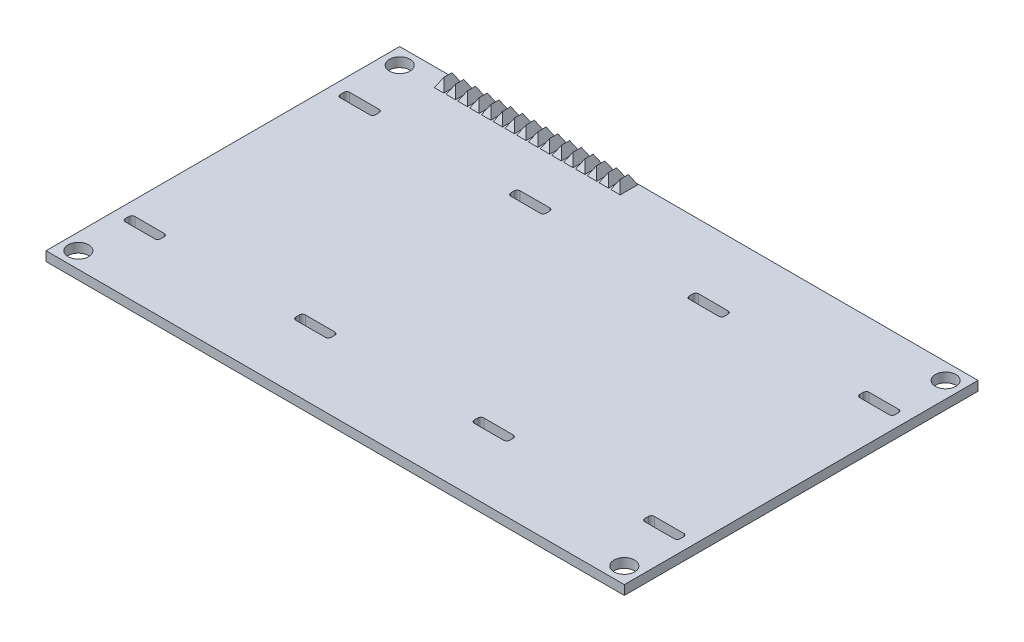
SolidWorks part; units mm, degrees
ref_plane "Front Plane" through (0, 0, 0) normal (0, 0, 1) x (1, 0, 0)
ref_plane "Top Plane" through (0, 0, 0) normal (0, 1, 0) x (1, 0, 0)
ref_plane "Right Plane" through (0, 0, 0) normal (1, 0, 0) x (0, 0, -1)
sketch "Sketch1" plane through (0, 0, 0) normal (0, 1, 0) x (1, 0, 0)
  line L0 (1, 57.4) -> (1, 50.0873) construction
  line L1 (0, 0) -> (98.35, 0)
  line L2 (0, 0) -> (0, 60.15)
  line L3 (0, 60.15) -> (98.35, 60.15)
  line L4 (98.35, 0) -> (98.35, 60.15)
  line L5 (2.75, 59.15) -> (12.6267, 59.15) construction
  line L6 (11, 60.05) -> (12.6, 60.05)
  line L7 (9, 60.05) -> (10.6, 60.05)
  line L8 (9, 60.05) -> (9, 57.05)
  line L9 (9, 57.05) -> (10.6, 57.05)
  line L10 (10.6, 60.05) -> (10.6, 57.05)
  line L11 (12.6, 60.05) -> (12.6, 57.05)
  line L12 (11, 57.05) -> (12.6, 57.05)
  line L13 (11, 60.05) -> (11, 57.05)
  line L14 (13, 60.05) -> (14.6, 60.05)
  line L15 (14.6, 60.05) -> (14.6, 57.05)
  line L16 (13, 57.05) -> (14.6, 57.05)
  line L17 (13, 60.05) -> (13, 57.05)
  line L18 (15, 60.05) -> (16.6, 60.05)
  line L19 (16.6, 60.05) -> (16.6, 57.05)
  line L20 (15, 57.05) -> (16.6, 57.05)
  line L21 (15, 60.05) -> (15, 57.05)
  line L22 (17, 60.05) -> (18.6, 60.05)
  line L23 (18.6, 60.05) -> (18.6, 57.05)
  line L24 (17, 57.05) -> (18.6, 57.05)
  line L25 (17, 60.05) -> (17, 57.05)
  line L26 (19, 60.05) -> (20.6, 60.05)
  line L27 (20.6, 60.05) -> (20.6, 57.05)
  line L28 (19, 57.05) -> (20.6, 57.05)
  line L29 (19, 60.05) -> (19, 57.05)
  line L30 (21, 60.05) -> (22.6, 60.05)
  line L31 (22.6, 60.05) -> (22.6, 57.05)
  line L32 (21, 57.05) -> (22.6, 57.05)
  line L33 (21, 60.05) -> (21, 57.05)
  line L34 (23, 60.05) -> (24.6, 60.05)
  line L35 (24.6, 60.05) -> (24.6, 57.05)
  line L36 (23, 57.05) -> (24.6, 57.05)
  line L37 (23, 60.05) -> (23, 57.05)
  line L38 (25, 60.05) -> (26.6, 60.05)
  line L39 (26.6, 60.05) -> (26.6, 57.05)
  line L40 (25, 57.05) -> (26.6, 57.05)
  line L41 (25, 60.05) -> (25, 57.05)
  line L42 (27, 60.05) -> (28.6, 60.05)
  line L43 (28.6, 60.05) -> (28.6, 57.05)
  line L44 (27, 57.05) -> (28.6, 57.05)
  line L45 (27, 60.05) -> (27, 57.05)
  line L46 (29, 60.05) -> (30.6, 60.05)
  line L47 (30.6, 60.05) -> (30.6, 57.05)
  line L48 (29, 57.05) -> (30.6, 57.05)
  line L49 (29, 60.05) -> (29, 57.05)
  line L50 (31, 60.05) -> (32.6, 60.05)
  line L51 (32.6, 60.05) -> (32.6, 57.05)
  line L52 (31, 57.05) -> (32.6, 57.05)
  line L53 (31, 60.05) -> (31, 57.05)
  line L54 (33, 60.05) -> (34.6, 60.05)
  line L55 (34.6, 60.05) -> (34.6, 57.05)
  line L56 (33, 57.05) -> (34.6, 57.05)
  line L57 (33, 60.05) -> (33, 57.05)
  line L58 (35, 60.05) -> (36.6, 60.05)
  line L59 (36.6, 60.05) -> (36.6, 57.05)
  line L60 (35, 57.05) -> (36.6, 57.05)
  line L61 (35, 60.05) -> (35, 57.05)
  line L62 (37, 60.05) -> (38.6, 60.05)
  line L63 (38.6, 60.05) -> (38.6, 57.05)
  line L64 (37, 57.05) -> (38.6, 57.05)
  line L65 (37, 60.05) -> (37, 57.05)
  line L66 (39, 60.05) -> (40.6, 60.05)
  line L67 (40.6, 60.05) -> (40.6, 57.05)
  line L68 (39, 57.05) -> (40.6, 57.05)
  line L69 (39, 60.05) -> (39, 57.05)
  line L70 (49.175, 60.15) -> (49.175, 0) construction
  line L71 (0, 30.075) -> (98.35, 30.075) construction
  line L72 (95.6, 59.15) -> (85.7233, 59.15) construction
  line L73 (97.35, 57.4) -> (97.35, 50.0873) construction
  line L74 (2.75, 1) -> (12.6267, 1) construction
  line L75 (1, 2.75) -> (1, 10.0627) construction
  line L76 (61.85, 49.15) -> (66.85, 49.15)
  line L77 (90.85, 49.15) -> (95.85, 49.15)
  line L78 (90.35, 48.65) -> (90.35, 48.05)
  line L79 (90.85, 47.55) -> (95.85, 47.55)
  line L80 (96.35, 48.65) -> (96.35, 48.05)
  line L81 (61.35, 48.65) -> (61.35, 48.05)
  line L82 (61.85, 47.55) -> (66.85, 47.55)
  line L83 (67.35, 48.65) -> (67.35, 48.05)
  line L84 (31, 48.65) -> (31, 48.05)
  line L85 (36.5, 47.55) -> (31.5, 47.55)
  line L86 (37, 48.65) -> (37, 48.05)
  line L87 (2, 48.65) -> (2, 48.05)
  line L88 (7.5, 47.55) -> (2.5, 47.55)
  line L89 (8, 48.65) -> (8, 48.05)
  line L90 (7.5, 49.15) -> (2.5, 49.15)
  line L91 (36.5, 49.15) -> (31.5, 49.15)
  line L92 (67.35, 11.5) -> (67.35, 12.1)
  line L93 (61.85, 12.6) -> (66.85, 12.6)
  line L94 (61.35, 11.5) -> (61.35, 12.1)
  line L95 (96.35, 11.5) -> (96.35, 12.1)
  line L96 (90.85, 12.6) -> (95.85, 12.6)
  line L97 (90.35, 11.5) -> (90.35, 12.1)
  line L98 (90.85, 11) -> (95.85, 11)
  line L99 (61.85, 11) -> (66.85, 11)
  line L100 (36.5, 11) -> (31.5, 11)
  line L101 (7.5, 11) -> (2.5, 11)
  line L102 (8, 11.5) -> (8, 12.1)
  line L103 (7.5, 12.6) -> (2.5, 12.6)
  line L104 (2, 11.5) -> (2, 12.1)
  line L105 (37, 11.5) -> (37, 12.1)
  line L106 (36.5, 12.6) -> (31.5, 12.6)
  line L107 (31, 11.5) -> (31, 12.1)
  circle A0 centre (2.75, 57.4) radius 1.75
  circle A1 centre (95.6, 57.4) radius 1.75
  circle A2 centre (95.6, 2.75) radius 1.75
  circle A3 centre (2.75, 2.75) radius 1.75
  arc A4 (95.85, 49.15) -> (96.35, 48.65) centre (95.85, 48.65) cw
  arc A5 (95.85, 47.55) -> (96.35, 48.05) centre (95.85, 48.05) ccw
  arc A6 (90.35, 48.05) -> (90.85, 47.55) centre (90.85, 48.05) ccw
  arc A7 (90.85, 49.15) -> (90.35, 48.65) centre (90.85, 48.65) ccw
  arc A8 (66.85, 49.15) -> (67.35, 48.65) centre (66.85, 48.65) cw
  arc A9 (66.85, 47.55) -> (67.35, 48.05) centre (66.85, 48.05) ccw
  arc A10 (61.35, 48.05) -> (61.85, 47.55) centre (61.85, 48.05) ccw
  arc A11 (61.85, 49.15) -> (61.35, 48.65) centre (61.85, 48.65) ccw
  arc A12 (36.5, 49.15) -> (37, 48.65) centre (36.5, 48.65) cw
  arc A13 (37, 48.05) -> (36.5, 47.55) centre (36.5, 48.05) cw
  arc A14 (31.5, 47.55) -> (31, 48.05) centre (31.5, 48.05) cw
  arc A15 (31.5, 49.15) -> (31, 48.65) centre (31.5, 48.65) ccw
  arc A16 (7.5, 49.15) -> (8, 48.65) centre (7.5, 48.65) cw
  arc A17 (8, 48.05) -> (7.5, 47.55) centre (7.5, 48.05) cw
  arc A18 (2.5, 47.55) -> (2, 48.05) centre (2.5, 48.05) cw
  arc A19 (2.5, 49.15) -> (2, 48.65) centre (2.5, 48.65) ccw
  arc A20 (61.85, 11) -> (61.35, 11.5) centre (61.85, 11.5) cw
  arc A21 (61.35, 12.1) -> (61.85, 12.6) centre (61.85, 12.1) cw
  arc A22 (66.85, 12.6) -> (67.35, 12.1) centre (66.85, 12.1) cw
  arc A23 (66.85, 11) -> (67.35, 11.5) centre (66.85, 11.5) ccw
  arc A24 (90.85, 11) -> (90.35, 11.5) centre (90.85, 11.5) cw
  arc A25 (90.35, 12.1) -> (90.85, 12.6) centre (90.85, 12.1) cw
  arc A26 (95.85, 12.6) -> (96.35, 12.1) centre (95.85, 12.1) cw
  arc A27 (95.85, 11) -> (96.35, 11.5) centre (95.85, 11.5) ccw
  arc A28 (2.5, 11) -> (2, 11.5) centre (2.5, 11.5) cw
  arc A29 (2.5, 12.6) -> (2, 12.1) centre (2.5, 12.1) ccw
  arc A30 (8, 12.1) -> (7.5, 12.6) centre (7.5, 12.1) ccw
  arc A31 (7.5, 11) -> (8, 11.5) centre (7.5, 11.5) ccw
  arc A32 (31.5, 11) -> (31, 11.5) centre (31.5, 11.5) cw
  arc A33 (31.5, 12.6) -> (31, 12.1) centre (31.5, 12.1) ccw
  arc A34 (37, 12.1) -> (36.5, 12.6) centre (36.5, 12.1) ccw
  arc A35 (36.5, 11) -> (37, 11.5) centre (36.5, 11.5) ccw
  point P99 (96.35, 49.15)
  point P102 (96.35, 47.55)
  point P107 (90.35, 49.15)
  point P108 (64.35, 49.15)
  point P109 (93.35, 49.15)
  point P146 (8, 49.15)
  point P147 (2, 47.55)
  point P148 (2, 49.15)
  point P173 (90.35, 11)
  point P174 (96.35, 12.6)
  point P175 (96.35, 11)
  point P200 (2, 11)
  point P201 (2, 12.6)
  point P202 (8, 11)
  dimension "D3" = 3.5
  dimension "D17" = 0.5
  dimension "D1" = 98.35
  dimension "D2" = 60.15
  dimension "D4" = 1
  dimension "D5" = 1
  dimension "D6" = 9
  dimension "D7" = 1.6
  dimension "D8" = 3
  dimension "D10" = 0.1
  dimension "D11" = 0.1
  dimension "D12" = 0.4
  dimension "D13" = 11
  dimension "D14" = 6
  dimension "D15" = 1.6
  dimension "D16" = 2
  dimension "D19" = 29
  dimension "D20" = 11
  dimension "D9" = 16
  dimension "D18" = 2
extrude "Boss-Extrude1" add sketch "Sketch1" along normal blind 1.6 contours L10 L7 L8 L9 | L6 L13 L12 L11 | L14 L17 L16 L15 | L18 L21 L20 L19 | L22 L25 L24 L23 | L30 L33 L32 L31 | L26 L29 L28 L27 | L34 L37 L36 L35 | L38 L41 L40 L39 | L42 L45 L44 L43 | L46 L49 L48 L47 | L50 L53 L52 L51 | L54 L57 L56 L55 | L58 L61 L60 L59 | L62 L65 L64 L63 | L66 L69 L68 L67 | L1 L4 L3 L2 A35 L100 A32 L107 A33 L106 A34 L105 A31 L101 A28 L104 A29 L103 A30 L102 A27 L98 A24 L97 A25 L96 A26 L95 A23 L99 A20 L94 A21 L93 A22 L92 A19 L90 A16 L89 A17 L88 A18 L87 A15
sketch "Sketch2" plane through (0, 1.6, 0) normal (0, 1, 0) x (1, 0, 0)
  line L4 (0, 0) -> (98.35, 0)
  line L5 (98.35, 0) -> (98.35, 60.15)
  line L6 (98.35, 60.15) -> (0, 60.15)
  line L7 (0, 60.15) -> (0, 0)
  line L8 (0, 0) -> (98.35, 0)
  line L9 (98.35, 0) -> (98.35, 60.15)
  line L10 (98.35, 60.15) -> (0, 60.15)
  line L11 (0, 60.15) -> (0, 0)
  line L12 (10.6, 60.05) -> (9, 60.05)
  line L13 (10.6, 57.05) -> (10.6, 60.05)
  line L14 (9, 57.05) -> (10.6, 57.05)
  line L15 (9, 60.05) -> (9, 57.05)
  line L16 (10.6, 60.05) -> (9, 60.05)
  line L17 (10.6, 57.05) -> (10.6, 60.05)
  line L18 (9, 57.05) -> (10.6, 57.05)
  line L19 (9, 60.05) -> (9, 57.05)
  line L20 (0, 0) -> (98.35, 0)
  line L21 (98.35, 0) -> (98.35, 60.15)
  line L22 (98.35, 60.15) -> (0, 60.15)
  line L23 (0, 60.15) -> (0, 0)
  line L24 (0, 0) -> (98.35, 0)
  line L25 (98.35, 0) -> (98.35, 60.15)
  line L26 (98.35, 60.15) -> (0, 60.15)
  line L27 (0, 60.15) -> (0, 0)
  line L28 (16.6, 60.05) -> (15, 60.05)
  line L29 (16.6, 57.05) -> (16.6, 60.05)
  line L30 (15, 57.05) -> (16.6, 57.05)
  line L31 (15, 60.05) -> (15, 57.05)
  line L32 (16.6, 60.05) -> (15, 60.05)
  line L33 (16.6, 57.05) -> (16.6, 60.05)
  line L34 (15, 57.05) -> (16.6, 57.05)
  line L35 (15, 60.05) -> (15, 57.05)
  line L36 (14.6, 60.05) -> (13, 60.05)
  line L37 (14.6, 57.05) -> (14.6, 60.05)
  line L38 (13, 57.05) -> (14.6, 57.05)
  line L39 (13, 60.05) -> (13, 57.05)
  line L40 (14.6, 60.05) -> (13, 60.05)
  line L41 (14.6, 57.05) -> (14.6, 60.05)
  line L42 (13, 57.05) -> (14.6, 57.05)
  line L43 (13, 60.05) -> (13, 57.05)
  line L44 (12.6, 60.05) -> (11, 60.05)
  line L45 (12.6, 57.05) -> (12.6, 60.05)
  line L46 (11, 57.05) -> (12.6, 57.05)
  line L47 (11, 60.05) -> (11, 57.05)
  line L48 (12.6, 60.05) -> (11, 60.05)
  line L49 (12.6, 57.05) -> (12.6, 60.05)
  line L50 (11, 57.05) -> (12.6, 57.05)
  line L51 (11, 60.05) -> (11, 57.05)
  line L52 (24.6, 60.05) -> (23, 60.05)
  line L53 (24.6, 57.05) -> (24.6, 60.05)
  line L54 (23, 57.05) -> (24.6, 57.05)
  line L55 (23, 60.05) -> (23, 57.05)
  line L56 (24.6, 60.05) -> (23, 60.05)
  line L57 (24.6, 57.05) -> (24.6, 60.05)
  line L58 (23, 57.05) -> (24.6, 57.05)
  line L59 (23, 60.05) -> (23, 57.05)
  line L60 (22.6, 60.05) -> (21, 60.05)
  line L61 (22.6, 57.05) -> (22.6, 60.05)
  line L62 (21, 57.05) -> (22.6, 57.05)
  line L63 (21, 60.05) -> (21, 57.05)
  line L64 (22.6, 60.05) -> (21, 60.05)
  line L65 (22.6, 57.05) -> (22.6, 60.05)
  line L66 (21, 57.05) -> (22.6, 57.05)
  line L67 (21, 60.05) -> (21, 57.05)
  line L68 (20.6, 60.05) -> (19, 60.05)
  line L69 (20.6, 57.05) -> (20.6, 60.05)
  line L70 (19, 57.05) -> (20.6, 57.05)
  line L71 (19, 60.05) -> (19, 57.05)
  line L72 (20.6, 60.05) -> (19, 60.05)
  line L73 (20.6, 57.05) -> (20.6, 60.05)
  line L74 (19, 57.05) -> (20.6, 57.05)
  line L75 (19, 60.05) -> (19, 57.05)
  line L76 (18.6, 60.05) -> (17, 60.05)
  line L77 (17, 60.05) -> (17, 57.05)
  line L78 (17, 57.05) -> (18.6, 57.05)
  line L79 (18.6, 57.05) -> (18.6, 60.05)
  line L80 (18.6, 60.05) -> (17, 60.05)
  line L81 (17, 60.05) -> (17, 57.05)
  line L82 (17, 57.05) -> (18.6, 57.05)
  line L83 (18.6, 57.05) -> (18.6, 60.05)
  line L84 (32.6, 60.05) -> (31, 60.05)
  line L85 (32.6, 57.05) -> (32.6, 60.05)
  line L86 (31, 57.05) -> (32.6, 57.05)
  line L87 (31, 60.05) -> (31, 57.05)
  line L88 (32.6, 60.05) -> (31, 60.05)
  line L89 (32.6, 57.05) -> (32.6, 60.05)
  line L90 (31, 57.05) -> (32.6, 57.05)
  line L91 (31, 60.05) -> (31, 57.05)
  line L92 (30.6, 60.05) -> (29, 60.05)
  line L93 (30.6, 57.05) -> (30.6, 60.05)
  line L94 (29, 57.05) -> (30.6, 57.05)
  line L95 (29, 60.05) -> (29, 57.05)
  line L96 (30.6, 60.05) -> (29, 60.05)
  line L97 (30.6, 57.05) -> (30.6, 60.05)
  line L98 (29, 57.05) -> (30.6, 57.05)
  line L99 (29, 60.05) -> (29, 57.05)
  line L100 (28.6, 60.05) -> (27, 60.05)
  line L101 (28.6, 57.05) -> (28.6, 60.05)
  line L102 (27, 57.05) -> (28.6, 57.05)
  line L103 (27, 60.05) -> (27, 57.05)
  line L104 (28.6, 60.05) -> (27, 60.05)
  line L105 (28.6, 57.05) -> (28.6, 60.05)
  line L106 (27, 57.05) -> (28.6, 57.05)
  line L107 (27, 60.05) -> (27, 57.05)
  line L108 (26.6, 60.05) -> (25, 60.05)
  line L109 (25, 60.05) -> (25, 57.05)
  line L110 (25, 57.05) -> (26.6, 57.05)
  line L111 (26.6, 57.05) -> (26.6, 60.05)
  line L112 (26.6, 60.05) -> (25, 60.05)
  line L113 (25, 60.05) -> (25, 57.05)
  line L114 (25, 57.05) -> (26.6, 57.05)
  line L115 (26.6, 57.05) -> (26.6, 60.05)
  line L116 (40.6, 60.05) -> (39, 60.05)
  line L117 (40.6, 57.05) -> (40.6, 60.05)
  line L118 (39, 57.05) -> (40.6, 57.05)
  line L119 (39, 60.05) -> (39, 57.05)
  line L120 (40.6, 60.05) -> (39, 60.05)
  line L121 (40.6, 57.05) -> (40.6, 60.05)
  line L122 (39, 57.05) -> (40.6, 57.05)
  line L123 (39, 60.05) -> (39, 57.05)
  line L124 (38.6, 60.05) -> (37, 60.05)
  line L125 (38.6, 57.05) -> (38.6, 60.05)
  line L126 (37, 57.05) -> (38.6, 57.05)
  line L127 (37, 60.05) -> (37, 57.05)
  line L128 (38.6, 60.05) -> (37, 60.05)
  line L129 (38.6, 57.05) -> (38.6, 60.05)
  line L130 (37, 57.05) -> (38.6, 57.05)
  line L131 (37, 60.05) -> (37, 57.05)
  line L132 (36.6, 60.05) -> (35, 60.05)
  line L133 (36.6, 57.05) -> (36.6, 60.05)
  line L134 (35, 57.05) -> (36.6, 57.05)
  line L135 (35, 60.05) -> (35, 57.05)
  line L136 (36.6, 60.05) -> (35, 60.05)
  line L137 (36.6, 57.05) -> (36.6, 60.05)
  line L138 (35, 57.05) -> (36.6, 57.05)
  line L139 (35, 60.05) -> (35, 57.05)
  line L140 (34.6, 60.05) -> (33, 60.05)
  line L141 (33, 60.05) -> (33, 57.05)
  line L142 (33, 57.05) -> (34.6, 57.05)
  line L143 (34.6, 57.05) -> (34.6, 60.05)
  line L144 (34.6, 60.05) -> (33, 60.05)
  line L145 (33, 60.05) -> (33, 57.05)
  line L146 (33, 57.05) -> (34.6, 57.05)
  line L147 (34.6, 57.05) -> (34.6, 60.05)
  line L148 (95.85, 49.15) -> (90.85, 49.15)
  line L149 (96.35, 48.05) -> (96.35, 48.65)
  line L150 (90.85, 47.55) -> (95.85, 47.55)
  line L151 (90.35, 48.65) -> (90.35, 48.05)
  line L152 (95.85, 49.15) -> (90.85, 49.15)
  line L153 (96.35, 48.05) -> (96.35, 48.65)
  line L154 (90.85, 47.55) -> (95.85, 47.55)
  line L155 (90.35, 48.65) -> (90.35, 48.05)
  line L156 (66.85, 49.15) -> (61.85, 49.15)
  line L157 (67.35, 48.05) -> (67.35, 48.65)
  line L158 (61.85, 47.55) -> (66.85, 47.55)
  line L159 (61.35, 48.65) -> (61.35, 48.05)
  line L160 (66.85, 49.15) -> (61.85, 49.15)
  line L161 (67.35, 48.05) -> (67.35, 48.65)
  line L162 (61.85, 47.55) -> (66.85, 47.55)
  line L163 (61.35, 48.65) -> (61.35, 48.05)
  line L164 (31, 48.65) -> (31, 48.05)
  line L165 (31.5, 47.55) -> (36.5, 47.55)
  line L166 (37, 48.05) -> (37, 48.65)
  line L167 (36.5, 49.15) -> (31.5, 49.15)
  line L168 (31, 48.65) -> (31, 48.05)
  line L169 (31.5, 47.55) -> (36.5, 47.55)
  line L170 (37, 48.05) -> (37, 48.65)
  line L171 (36.5, 49.15) -> (31.5, 49.15)
  line L172 (2, 48.65) -> (2, 48.05)
  line L173 (2.5, 47.55) -> (7.5, 47.55)
  line L174 (8, 48.05) -> (8, 48.65)
  line L175 (7.5, 49.15) -> (2.5, 49.15)
  line L176 (2, 48.65) -> (2, 48.05)
  line L177 (2.5, 47.55) -> (7.5, 47.55)
  line L178 (8, 48.05) -> (8, 48.65)
  line L179 (7.5, 49.15) -> (2.5, 49.15)
  line L180 (96.35, 11.5) -> (96.35, 12.1)
  line L181 (95.85, 12.6) -> (90.85, 12.6)
  line L182 (90.35, 12.1) -> (90.35, 11.5)
  line L183 (90.85, 11) -> (95.85, 11)
  line L184 (96.35, 11.5) -> (96.35, 12.1)
  line L185 (95.85, 12.6) -> (90.85, 12.6)
  line L186 (90.35, 12.1) -> (90.35, 11.5)
  line L187 (90.85, 11) -> (95.85, 11)
  line L188 (67.35, 11.5) -> (67.35, 12.1)
  line L189 (66.85, 12.6) -> (61.85, 12.6)
  line L190 (61.35, 12.1) -> (61.35, 11.5)
  line L191 (61.85, 11) -> (66.85, 11)
  line L192 (67.35, 11.5) -> (67.35, 12.1)
  line L193 (66.85, 12.6) -> (61.85, 12.6)
  line L194 (61.35, 12.1) -> (61.35, 11.5)
  line L195 (61.85, 11) -> (66.85, 11)
  line L196 (2.5, 11) -> (7.5, 11)
  line L197 (2, 12.1) -> (2, 11.5)
  line L198 (7.5, 12.6) -> (2.5, 12.6)
  line L199 (8, 11.5) -> (8, 12.1)
  line L200 (2.5, 11) -> (7.5, 11)
  line L201 (2, 12.1) -> (2, 11.5)
  line L202 (7.5, 12.6) -> (2.5, 12.6)
  line L203 (8, 11.5) -> (8, 12.1)
  line L204 (31.5, 11) -> (36.5, 11)
  line L205 (31, 12.1) -> (31, 11.5)
  line L206 (36.5, 12.6) -> (31.5, 12.6)
  line L207 (37, 11.5) -> (37, 12.1)
  line L208 (31.5, 11) -> (36.5, 11)
  line L209 (31, 12.1) -> (31, 11.5)
  line L210 (36.5, 12.6) -> (31.5, 12.6)
  line L211 (37, 11.5) -> (37, 12.1)
  circle A1 centre (2.75, 57.4) radius 1.75
  circle A2 centre (2.75, 57.4) radius 1.75
  circle A3 centre (2.75, 2.75) radius 1.75
  circle A4 centre (2.75, 2.75) radius 1.75
  circle A5 centre (95.6, 2.75) radius 1.75
  circle A6 centre (95.6, 2.75) radius 1.75
  circle A7 centre (95.6, 57.4) radius 1.75
  circle A8 centre (95.6, 57.4) radius 1.75
  arc A12 (96.35, 48.65) -> (95.85, 49.15) centre (95.85, 48.65) ccw
  arc A13 (95.85, 47.55) -> (96.35, 48.05) centre (95.85, 48.05) ccw
  arc A14 (90.35, 48.05) -> (90.85, 47.55) centre (90.85, 48.05) ccw
  arc A15 (90.85, 49.15) -> (90.35, 48.65) centre (90.85, 48.65) ccw
  arc A16 (96.35, 48.65) -> (95.85, 49.15) centre (95.85, 48.65) ccw
  arc A17 (95.85, 47.55) -> (96.35, 48.05) centre (95.85, 48.05) ccw
  arc A18 (90.35, 48.05) -> (90.85, 47.55) centre (90.85, 48.05) ccw
  arc A19 (90.85, 49.15) -> (90.35, 48.65) centre (90.85, 48.65) ccw
  arc A20 (67.35, 48.65) -> (66.85, 49.15) centre (66.85, 48.65) ccw
  arc A21 (66.85, 47.55) -> (67.35, 48.05) centre (66.85, 48.05) ccw
  arc A22 (61.35, 48.05) -> (61.85, 47.55) centre (61.85, 48.05) ccw
  arc A23 (61.85, 49.15) -> (61.35, 48.65) centre (61.85, 48.65) ccw
  arc A24 (67.35, 48.65) -> (66.85, 49.15) centre (66.85, 48.65) ccw
  arc A25 (66.85, 47.55) -> (67.35, 48.05) centre (66.85, 48.05) ccw
  arc A26 (61.35, 48.05) -> (61.85, 47.55) centre (61.85, 48.05) ccw
  arc A27 (61.85, 49.15) -> (61.35, 48.65) centre (61.85, 48.65) ccw
  arc A28 (31, 48.05) -> (31.5, 47.55) centre (31.5, 48.05) ccw
  arc A29 (36.5, 47.55) -> (37, 48.05) centre (36.5, 48.05) ccw
  arc A30 (37, 48.65) -> (36.5, 49.15) centre (36.5, 48.65) ccw
  arc A31 (31.5, 49.15) -> (31, 48.65) centre (31.5, 48.65) ccw
  arc A32 (31, 48.05) -> (31.5, 47.55) centre (31.5, 48.05) ccw
  arc A33 (36.5, 47.55) -> (37, 48.05) centre (36.5, 48.05) ccw
  arc A34 (37, 48.65) -> (36.5, 49.15) centre (36.5, 48.65) ccw
  arc A35 (31.5, 49.15) -> (31, 48.65) centre (31.5, 48.65) ccw
  arc A36 (2, 48.05) -> (2.5, 47.55) centre (2.5, 48.05) ccw
  arc A37 (7.5, 47.55) -> (8, 48.05) centre (7.5, 48.05) ccw
  arc A38 (8, 48.65) -> (7.5, 49.15) centre (7.5, 48.65) ccw
  arc A39 (2.5, 49.15) -> (2, 48.65) centre (2.5, 48.65) ccw
  arc A40 (2, 48.05) -> (2.5, 47.55) centre (2.5, 48.05) ccw
  arc A41 (7.5, 47.55) -> (8, 48.05) centre (7.5, 48.05) ccw
  arc A42 (8, 48.65) -> (7.5, 49.15) centre (7.5, 48.65) ccw
  arc A43 (2.5, 49.15) -> (2, 48.65) centre (2.5, 48.65) ccw
  arc A44 (96.35, 12.1) -> (95.85, 12.6) centre (95.85, 12.1) ccw
  arc A45 (90.85, 12.6) -> (90.35, 12.1) centre (90.85, 12.1) ccw
  arc A46 (90.35, 11.5) -> (90.85, 11) centre (90.85, 11.5) ccw
  arc A47 (95.85, 11) -> (96.35, 11.5) centre (95.85, 11.5) ccw
  arc A48 (96.35, 12.1) -> (95.85, 12.6) centre (95.85, 12.1) ccw
  arc A49 (90.85, 12.6) -> (90.35, 12.1) centre (90.85, 12.1) ccw
  arc A50 (90.35, 11.5) -> (90.85, 11) centre (90.85, 11.5) ccw
  arc A51 (95.85, 11) -> (96.35, 11.5) centre (95.85, 11.5) ccw
  arc A52 (67.35, 12.1) -> (66.85, 12.6) centre (66.85, 12.1) ccw
  arc A53 (61.85, 12.6) -> (61.35, 12.1) centre (61.85, 12.1) ccw
  arc A54 (61.35, 11.5) -> (61.85, 11) centre (61.85, 11.5) ccw
  arc A55 (66.85, 11) -> (67.35, 11.5) centre (66.85, 11.5) ccw
  arc A56 (67.35, 12.1) -> (66.85, 12.6) centre (66.85, 12.1) ccw
  arc A57 (61.85, 12.6) -> (61.35, 12.1) centre (61.85, 12.1) ccw
  arc A58 (61.35, 11.5) -> (61.85, 11) centre (61.85, 11.5) ccw
  arc A59 (66.85, 11) -> (67.35, 11.5) centre (66.85, 11.5) ccw
  arc A60 (2, 11.5) -> (2.5, 11) centre (2.5, 11.5) ccw
  arc A61 (2.5, 12.6) -> (2, 12.1) centre (2.5, 12.1) ccw
  arc A62 (8, 12.1) -> (7.5, 12.6) centre (7.5, 12.1) ccw
  arc A63 (7.5, 11) -> (8, 11.5) centre (7.5, 11.5) ccw
  arc A64 (2, 11.5) -> (2.5, 11) centre (2.5, 11.5) ccw
  arc A65 (2.5, 12.6) -> (2, 12.1) centre (2.5, 12.1) ccw
  arc A66 (8, 12.1) -> (7.5, 12.6) centre (7.5, 12.1) ccw
  arc A67 (7.5, 11) -> (8, 11.5) centre (7.5, 11.5) ccw
  arc A68 (31, 11.5) -> (31.5, 11) centre (31.5, 11.5) ccw
  arc A69 (31.5, 12.6) -> (31, 12.1) centre (31.5, 12.1) ccw
  arc A70 (37, 12.1) -> (36.5, 12.6) centre (36.5, 12.1) ccw
  arc A71 (36.5, 11) -> (37, 11.5) centre (36.5, 11.5) ccw
  arc A72 (31, 11.5) -> (31.5, 11) centre (31.5, 11.5) ccw
  arc A73 (31.5, 12.6) -> (31, 12.1) centre (31.5, 12.1) ccw
  arc A74 (37, 12.1) -> (36.5, 12.6) centre (36.5, 12.1) ccw
  arc A75 (36.5, 11) -> (37, 11.5) centre (36.5, 11.5) ccw
  dimension "D1" = 0
  dimension "D2" = 0
  dimension "D3" = 0
  dimension "D4" = 0
  dimension "D5" = 0
  dimension "D6" = 0
  dimension "D7" = 0
  dimension "D8" = 0
  dimension "D9" = 0
  dimension "D10" = 0
  dimension "D11" = 0
  dimension "D12" = 0
  dimension "D13" = 0
  dimension "D14" = 0
  dimension "D15" = 0
  dimension "D16" = 0
  dimension "D17" = 0
  dimension "D18" = 0
  dimension "D19" = 0
  dimension "D20" = 0
  dimension "D21" = 0
  dimension "D22" = 0
  dimension "D23" = 0
  dimension "D24" = 0
  dimension "D25" = 0
  dimension "D26" = 0
  dimension "D27" = 0
  dimension "D28" = 0
  dimension "D29" = 0
  dimension "D30" = 0
extrude "Boss-Extrude2" add sketch "Sketch2" along normal blind 1.6 draft 28 contours L16 L19 L18 L17 | L48 L51 L50 L49 | L40 L43 L42 L41 | L32 L35 L34 L33 | L82 L83 L80 L81 | L72 L75 L74 L73 | L64 L67 L66 L65 | L56 L59 L58 L57 | L114 L115 L112 L113 | L104 L107 L106 L105 | L96 L99 L98 L97 | L88 L91 L90 L89 | L146 L147 L144 L145 | L136 L139 L138 L137 | L128 L131 L130 L129 | L120 L123 L122 L121
sketch "Sketch3" plane through (0, 0, 0) normal (0, -1, 0) x (1, 0, 0)
  line L4 (9, -60.05) -> (10.6, -60.05)
  line L5 (10.6, -60.05) -> (10.6, -57.05)
  line L6 (10.6, -57.05) -> (9, -57.05)
  line L7 (9, -57.05) -> (9, -60.05)
  line L8 (9, -60.05) -> (10.6, -60.05)
  line L9 (10.6, -60.05) -> (10.6, -57.05)
  line L10 (10.6, -57.05) -> (9, -57.05)
  line L11 (9, -57.05) -> (9, -60.05)
  line L12 (98.35, 0) -> (0, 0)
  line L13 (98.35, -60.15) -> (98.35, 0)
  line L14 (0, -60.15) -> (98.35, -60.15)
  line L15 (0, 0) -> (0, -60.15)
  line L16 (98.35, 0) -> (0, 0)
  line L17 (98.35, -60.15) -> (98.35, 0)
  line L18 (0, -60.15) -> (98.35, -60.15)
  line L19 (0, 0) -> (0, -60.15)
  line L20 (15, -60.05) -> (16.6, -60.05)
  line L21 (16.6, -60.05) -> (16.6, -57.05)
  line L22 (16.6, -57.05) -> (15, -57.05)
  line L23 (15, -57.05) -> (15, -60.05)
  line L24 (15, -60.05) -> (16.6, -60.05)
  line L25 (16.6, -60.05) -> (16.6, -57.05)
  line L26 (16.6, -57.05) -> (15, -57.05)
  line L27 (15, -57.05) -> (15, -60.05)
  line L28 (13, -60.05) -> (14.6, -60.05)
  line L29 (14.6, -60.05) -> (14.6, -57.05)
  line L30 (14.6, -57.05) -> (13, -57.05)
  line L31 (13, -57.05) -> (13, -60.05)
  line L32 (13, -60.05) -> (14.6, -60.05)
  line L33 (14.6, -60.05) -> (14.6, -57.05)
  line L34 (14.6, -57.05) -> (13, -57.05)
  line L35 (13, -57.05) -> (13, -60.05)
  line L36 (11, -60.05) -> (12.6, -60.05)
  line L37 (12.6, -60.05) -> (12.6, -57.05)
  line L38 (12.6, -57.05) -> (11, -57.05)
  line L39 (11, -57.05) -> (11, -60.05)
  line L40 (11, -60.05) -> (12.6, -60.05)
  line L41 (12.6, -60.05) -> (12.6, -57.05)
  line L42 (12.6, -57.05) -> (11, -57.05)
  line L43 (11, -57.05) -> (11, -60.05)
  line L44 (23, -60.05) -> (24.6, -60.05)
  line L45 (24.6, -60.05) -> (24.6, -57.05)
  line L46 (24.6, -57.05) -> (23, -57.05)
  line L47 (23, -57.05) -> (23, -60.05)
  line L48 (23, -60.05) -> (24.6, -60.05)
  line L49 (24.6, -60.05) -> (24.6, -57.05)
  line L50 (24.6, -57.05) -> (23, -57.05)
  line L51 (23, -57.05) -> (23, -60.05)
  line L52 (21, -60.05) -> (22.6, -60.05)
  line L53 (22.6, -60.05) -> (22.6, -57.05)
  line L54 (22.6, -57.05) -> (21, -57.05)
  line L55 (21, -57.05) -> (21, -60.05)
  line L56 (21, -60.05) -> (22.6, -60.05)
  line L57 (22.6, -60.05) -> (22.6, -57.05)
  line L58 (22.6, -57.05) -> (21, -57.05)
  line L59 (21, -57.05) -> (21, -60.05)
  line L60 (19, -60.05) -> (20.6, -60.05)
  line L61 (20.6, -60.05) -> (20.6, -57.05)
  line L62 (20.6, -57.05) -> (19, -57.05)
  line L63 (19, -57.05) -> (19, -60.05)
  line L64 (19, -60.05) -> (20.6, -60.05)
  line L65 (20.6, -60.05) -> (20.6, -57.05)
  line L66 (20.6, -57.05) -> (19, -57.05)
  line L67 (19, -57.05) -> (19, -60.05)
  line L68 (17, -60.05) -> (18.6, -60.05)
  line L69 (17, -57.05) -> (17, -60.05)
  line L70 (18.6, -57.05) -> (17, -57.05)
  line L71 (18.6, -60.05) -> (18.6, -57.05)
  line L72 (17, -60.05) -> (18.6, -60.05)
  line L73 (17, -57.05) -> (17, -60.05)
  line L74 (18.6, -57.05) -> (17, -57.05)
  line L75 (18.6, -60.05) -> (18.6, -57.05)
  line L76 (31, -60.05) -> (32.6, -60.05)
  line L77 (32.6, -60.05) -> (32.6, -57.05)
  line L78 (32.6, -57.05) -> (31, -57.05)
  line L79 (31, -57.05) -> (31, -60.05)
  line L80 (31, -60.05) -> (32.6, -60.05)
  line L81 (32.6, -60.05) -> (32.6, -57.05)
  line L82 (32.6, -57.05) -> (31, -57.05)
  line L83 (31, -57.05) -> (31, -60.05)
  line L84 (29, -60.05) -> (30.6, -60.05)
  line L85 (30.6, -60.05) -> (30.6, -57.05)
  line L86 (30.6, -57.05) -> (29, -57.05)
  line L87 (29, -57.05) -> (29, -60.05)
  line L88 (29, -60.05) -> (30.6, -60.05)
  line L89 (30.6, -60.05) -> (30.6, -57.05)
  line L90 (30.6, -57.05) -> (29, -57.05)
  line L91 (29, -57.05) -> (29, -60.05)
  line L92 (27, -60.05) -> (28.6, -60.05)
  line L93 (28.6, -60.05) -> (28.6, -57.05)
  line L94 (28.6, -57.05) -> (27, -57.05)
  line L95 (27, -57.05) -> (27, -60.05)
  line L96 (27, -60.05) -> (28.6, -60.05)
  line L97 (28.6, -60.05) -> (28.6, -57.05)
  line L98 (28.6, -57.05) -> (27, -57.05)
  line L99 (27, -57.05) -> (27, -60.05)
  line L100 (25, -60.05) -> (26.6, -60.05)
  line L101 (25, -57.05) -> (25, -60.05)
  line L102 (26.6, -57.05) -> (25, -57.05)
  line L103 (26.6, -60.05) -> (26.6, -57.05)
  line L104 (25, -60.05) -> (26.6, -60.05)
  line L105 (25, -57.05) -> (25, -60.05)
  line L106 (26.6, -57.05) -> (25, -57.05)
  line L107 (26.6, -60.05) -> (26.6, -57.05)
  line L108 (39, -60.05) -> (40.6, -60.05)
  line L109 (40.6, -60.05) -> (40.6, -57.05)
  line L110 (40.6, -57.05) -> (39, -57.05)
  line L111 (39, -57.05) -> (39, -60.05)
  line L112 (39, -60.05) -> (40.6, -60.05)
  line L113 (40.6, -60.05) -> (40.6, -57.05)
  line L114 (40.6, -57.05) -> (39, -57.05)
  line L115 (39, -57.05) -> (39, -60.05)
  line L116 (37, -60.05) -> (38.6, -60.05)
  line L117 (38.6, -60.05) -> (38.6, -57.05)
  line L118 (38.6, -57.05) -> (37, -57.05)
  line L119 (37, -57.05) -> (37, -60.05)
  line L120 (37, -60.05) -> (38.6, -60.05)
  line L121 (38.6, -60.05) -> (38.6, -57.05)
  line L122 (38.6, -57.05) -> (37, -57.05)
  line L123 (37, -57.05) -> (37, -60.05)
  line L124 (35, -60.05) -> (36.6, -60.05)
  line L125 (36.6, -60.05) -> (36.6, -57.05)
  line L126 (36.6, -57.05) -> (35, -57.05)
  line L127 (35, -57.05) -> (35, -60.05)
  line L128 (35, -60.05) -> (36.6, -60.05)
  line L129 (36.6, -60.05) -> (36.6, -57.05)
  line L130 (36.6, -57.05) -> (35, -57.05)
  line L131 (35, -57.05) -> (35, -60.05)
  line L132 (33, -60.05) -> (34.6, -60.05)
  line L133 (33, -57.05) -> (33, -60.05)
  line L134 (34.6, -57.05) -> (33, -57.05)
  line L135 (34.6, -60.05) -> (34.6, -57.05)
  line L136 (33, -60.05) -> (34.6, -60.05)
  line L137 (33, -57.05) -> (33, -60.05)
  line L138 (34.6, -57.05) -> (33, -57.05)
  line L139 (34.6, -60.05) -> (34.6, -57.05)
  line L140 (90.85, -49.15) -> (95.85, -49.15)
  line L141 (96.35, -48.65) -> (96.35, -48.05)
  line L142 (95.85, -47.55) -> (90.85, -47.55)
  line L143 (90.35, -48.05) -> (90.35, -48.65)
  line L144 (90.85, -49.15) -> (95.85, -49.15)
  line L145 (96.35, -48.65) -> (96.35, -48.05)
  line L146 (95.85, -47.55) -> (90.85, -47.55)
  line L147 (90.35, -48.05) -> (90.35, -48.65)
  line L148 (61.85, -49.15) -> (66.85, -49.15)
  line L149 (67.35, -48.65) -> (67.35, -48.05)
  line L150 (66.85, -47.55) -> (61.85, -47.55)
  line L151 (61.35, -48.05) -> (61.35, -48.65)
  line L152 (61.85, -49.15) -> (66.85, -49.15)
  line L153 (67.35, -48.65) -> (67.35, -48.05)
  line L154 (66.85, -47.55) -> (61.85, -47.55)
  line L155 (61.35, -48.05) -> (61.35, -48.65)
  line L156 (31, -48.05) -> (31, -48.65)
  line L157 (36.5, -47.55) -> (31.5, -47.55)
  line L158 (37, -48.65) -> (37, -48.05)
  line L159 (31.5, -49.15) -> (36.5, -49.15)
  line L160 (31, -48.05) -> (31, -48.65)
  line L161 (36.5, -47.55) -> (31.5, -47.55)
  line L162 (37, -48.65) -> (37, -48.05)
  line L163 (31.5, -49.15) -> (36.5, -49.15)
  line L164 (2, -48.05) -> (2, -48.65)
  line L165 (7.5, -47.55) -> (2.5, -47.55)
  line L166 (8, -48.65) -> (8, -48.05)
  line L167 (2.5, -49.15) -> (7.5, -49.15)
  line L168 (2, -48.05) -> (2, -48.65)
  line L169 (7.5, -47.55) -> (2.5, -47.55)
  line L170 (8, -48.65) -> (8, -48.05)
  line L171 (2.5, -49.15) -> (7.5, -49.15)
  line L172 (96.35, -12.1) -> (96.35, -11.5)
  line L173 (90.85, -12.6) -> (95.85, -12.6)
  line L174 (90.35, -11.5) -> (90.35, -12.1)
  line L175 (95.85, -11) -> (90.85, -11)
  line L176 (96.35, -12.1) -> (96.35, -11.5)
  line L177 (90.85, -12.6) -> (95.85, -12.6)
  line L178 (90.35, -11.5) -> (90.35, -12.1)
  line L179 (95.85, -11) -> (90.85, -11)
  line L180 (67.35, -12.1) -> (67.35, -11.5)
  line L181 (61.85, -12.6) -> (66.85, -12.6)
  line L182 (61.35, -11.5) -> (61.35, -12.1)
  line L183 (66.85, -11) -> (61.85, -11)
  line L184 (67.35, -12.1) -> (67.35, -11.5)
  line L185 (61.85, -12.6) -> (66.85, -12.6)
  line L186 (61.35, -11.5) -> (61.35, -12.1)
  line L187 (66.85, -11) -> (61.85, -11)
  line L188 (7.5, -11) -> (2.5, -11)
  line L189 (2, -11.5) -> (2, -12.1)
  line L190 (2.5, -12.6) -> (7.5, -12.6)
  line L191 (8, -12.1) -> (8, -11.5)
  line L192 (7.5, -11) -> (2.5, -11)
  line L193 (2, -11.5) -> (2, -12.1)
  line L194 (2.5, -12.6) -> (7.5, -12.6)
  line L195 (8, -12.1) -> (8, -11.5)
  line L196 (36.5, -11) -> (31.5, -11)
  line L197 (31, -11.5) -> (31, -12.1)
  line L198 (31.5, -12.6) -> (36.5, -12.6)
  line L199 (37, -12.1) -> (37, -11.5)
  line L200 (36.5, -11) -> (31.5, -11)
  line L201 (31, -11.5) -> (31, -12.1)
  line L202 (31.5, -12.6) -> (36.5, -12.6)
  line L203 (37, -12.1) -> (37, -11.5)
  circle A0 centre (9.8, -58.55) radius 0.3
  circle A1 centre (2.75, -57.4) radius 1.75
  circle A2 centre (2.75, -57.4) radius 1.75
  circle A3 centre (2.75, -2.75) radius 1.75
  circle A4 centre (2.75, -2.75) radius 1.75
  circle A5 centre (95.6, -2.75) radius 1.75
  circle A6 centre (95.6, -2.75) radius 1.75
  circle A7 centre (95.6, -57.4) radius 1.75
  circle A8 centre (95.6, -57.4) radius 1.75
  arc A12 (95.85, -49.15) -> (96.35, -48.65) centre (95.85, -48.65) ccw
  arc A13 (96.35, -48.05) -> (95.85, -47.55) centre (95.85, -48.05) ccw
  arc A14 (90.85, -47.55) -> (90.35, -48.05) centre (90.85, -48.05) ccw
  arc A15 (90.35, -48.65) -> (90.85, -49.15) centre (90.85, -48.65) ccw
  arc A16 (95.85, -49.15) -> (96.35, -48.65) centre (95.85, -48.65) ccw
  arc A17 (96.35, -48.05) -> (95.85, -47.55) centre (95.85, -48.05) ccw
  arc A18 (90.85, -47.55) -> (90.35, -48.05) centre (90.85, -48.05) ccw
  arc A19 (90.35, -48.65) -> (90.85, -49.15) centre (90.85, -48.65) ccw
  arc A20 (66.85, -49.15) -> (67.35, -48.65) centre (66.85, -48.65) ccw
  arc A21 (67.35, -48.05) -> (66.85, -47.55) centre (66.85, -48.05) ccw
  arc A22 (61.85, -47.55) -> (61.35, -48.05) centre (61.85, -48.05) ccw
  arc A23 (61.35, -48.65) -> (61.85, -49.15) centre (61.85, -48.65) ccw
  arc A24 (66.85, -49.15) -> (67.35, -48.65) centre (66.85, -48.65) ccw
  arc A25 (67.35, -48.05) -> (66.85, -47.55) centre (66.85, -48.05) ccw
  arc A26 (61.85, -47.55) -> (61.35, -48.05) centre (61.85, -48.05) ccw
  arc A27 (61.35, -48.65) -> (61.85, -49.15) centre (61.85, -48.65) ccw
  arc A28 (31.5, -47.55) -> (31, -48.05) centre (31.5, -48.05) ccw
  arc A29 (37, -48.05) -> (36.5, -47.55) centre (36.5, -48.05) ccw
  arc A30 (36.5, -49.15) -> (37, -48.65) centre (36.5, -48.65) ccw
  arc A31 (31, -48.65) -> (31.5, -49.15) centre (31.5, -48.65) ccw
  arc A32 (31.5, -47.55) -> (31, -48.05) centre (31.5, -48.05) ccw
  arc A33 (37, -48.05) -> (36.5, -47.55) centre (36.5, -48.05) ccw
  arc A34 (36.5, -49.15) -> (37, -48.65) centre (36.5, -48.65) ccw
  arc A35 (31, -48.65) -> (31.5, -49.15) centre (31.5, -48.65) ccw
  arc A36 (2.5, -47.55) -> (2, -48.05) centre (2.5, -48.05) ccw
  arc A37 (8, -48.05) -> (7.5, -47.55) centre (7.5, -48.05) ccw
  arc A38 (7.5, -49.15) -> (8, -48.65) centre (7.5, -48.65) ccw
  arc A39 (2, -48.65) -> (2.5, -49.15) centre (2.5, -48.65) ccw
  arc A40 (2.5, -47.55) -> (2, -48.05) centre (2.5, -48.05) ccw
  arc A41 (8, -48.05) -> (7.5, -47.55) centre (7.5, -48.05) ccw
  arc A42 (7.5, -49.15) -> (8, -48.65) centre (7.5, -48.65) ccw
  arc A43 (2, -48.65) -> (2.5, -49.15) centre (2.5, -48.65) ccw
  arc A44 (95.85, -12.6) -> (96.35, -12.1) centre (95.85, -12.1) ccw
  arc A45 (90.35, -12.1) -> (90.85, -12.6) centre (90.85, -12.1) ccw
  arc A46 (90.85, -11) -> (90.35, -11.5) centre (90.85, -11.5) ccw
  arc A47 (96.35, -11.5) -> (95.85, -11) centre (95.85, -11.5) ccw
  arc A48 (95.85, -12.6) -> (96.35, -12.1) centre (95.85, -12.1) ccw
  arc A49 (90.35, -12.1) -> (90.85, -12.6) centre (90.85, -12.1) ccw
  arc A50 (90.85, -11) -> (90.35, -11.5) centre (90.85, -11.5) ccw
  arc A51 (96.35, -11.5) -> (95.85, -11) centre (95.85, -11.5) ccw
  arc A52 (66.85, -12.6) -> (67.35, -12.1) centre (66.85, -12.1) ccw
  arc A53 (61.35, -12.1) -> (61.85, -12.6) centre (61.85, -12.1) ccw
  arc A54 (61.85, -11) -> (61.35, -11.5) centre (61.85, -11.5) ccw
  arc A55 (67.35, -11.5) -> (66.85, -11) centre (66.85, -11.5) ccw
  arc A56 (66.85, -12.6) -> (67.35, -12.1) centre (66.85, -12.1) ccw
  arc A57 (61.35, -12.1) -> (61.85, -12.6) centre (61.85, -12.1) ccw
  arc A58 (61.85, -11) -> (61.35, -11.5) centre (61.85, -11.5) ccw
  arc A59 (67.35, -11.5) -> (66.85, -11) centre (66.85, -11.5) ccw
  arc A60 (2.5, -11) -> (2, -11.5) centre (2.5, -11.5) ccw
  arc A61 (2, -12.1) -> (2.5, -12.6) centre (2.5, -12.1) ccw
  arc A62 (7.5, -12.6) -> (8, -12.1) centre (7.5, -12.1) ccw
  arc A63 (8, -11.5) -> (7.5, -11) centre (7.5, -11.5) ccw
  arc A64 (2.5, -11) -> (2, -11.5) centre (2.5, -11.5) ccw
  arc A65 (2, -12.1) -> (2.5, -12.6) centre (2.5, -12.1) ccw
  arc A66 (7.5, -12.6) -> (8, -12.1) centre (7.5, -12.1) ccw
  arc A67 (8, -11.5) -> (7.5, -11) centre (7.5, -11.5) ccw
  arc A68 (31.5, -11) -> (31, -11.5) centre (31.5, -11.5) ccw
  arc A69 (31, -12.1) -> (31.5, -12.6) centre (31.5, -12.1) ccw
  arc A70 (36.5, -12.6) -> (37, -12.1) centre (36.5, -12.1) ccw
  arc A71 (37, -11.5) -> (36.5, -11) centre (36.5, -11.5) ccw
  arc A72 (31.5, -11) -> (31, -11.5) centre (31.5, -11.5) ccw
  arc A73 (31, -12.1) -> (31.5, -12.6) centre (31.5, -12.1) ccw
  arc A74 (36.5, -12.6) -> (37, -12.1) centre (36.5, -12.1) ccw
  arc A75 (37, -11.5) -> (36.5, -11) centre (36.5, -11.5) ccw
  point P172 (9.8, -57.05)
  point P175 (10.6, -58.55)
  dimension "D30" = 0.6
  dimension "D31" = 1.5
  dimension "D32" = 0.8
  dimension "D1" = 0
  dimension "D2" = 0
  dimension "D3" = 0
  dimension "D4" = 0
  dimension "D5" = 0
  dimension "D6" = 0
  dimension "D7" = 0
  dimension "D8" = 0
  dimension "D9" = 0
  dimension "D10" = 0
  dimension "D11" = 0
  dimension "D12" = 0
  dimension "D13" = 0
  dimension "D14" = 0
  dimension "D15" = 0
  dimension "D16" = 0
  dimension "D17" = 0
  dimension "D18" = 0
  dimension "D19" = 0
  dimension "D20" = 0
  dimension "D21" = 0
  dimension "D22" = 0
  dimension "D23" = 0
  dimension "D24" = 0
  dimension "D25" = 0
  dimension "D26" = 0
  dimension "D27" = 0
  dimension "D28" = 0
  dimension "D29" = 0
extrude "Boss-Extrude3" add sketch "Sketch3" along normal blind 5 contours A0
pattern_linear "LPattern1" count 16 spacing 2 along (1, 0, 0) of "Boss-Extrude3"
sketch "Sketch4" plane through (0, 0, 0) normal (0, -1, 0) x (1, 0, 0)
  line L1 (0, 0) -> (98.35, 0) construction
  line L2 (98.35, 0) -> (98.35, -60.15) construction
  circle A0 centre (78.35, -30) radius 5
  circle A1 centre (58.35, -36) radius 5
  circle A2 centre (53.35, -20) radius 5
  circle A3 centre (32.35, -36) radius 5
  circle A4 centre (23.35, -20) radius 5
  point P6 (98.35, -30.075)
  dimension "D1" = 10
  dimension "D4" = 10
  dimension "D7" = 10
  dimension "D8" = 45
  dimension "D9" = 20
  dimension "D10" = 10
  dimension "D14" = 10
  dimension "D2" = 20
  dimension "D3" = 30
  dimension "D5" = 40
  dimension "D6" = 36
  dimension "D11" = 36
  dimension "D12" = 66
  dimension "D13" = 75
  dimension "D15" = 20
extrude "Boss-Extrude4" add sketch "Sketch4" along normal blind 1 draft 79
